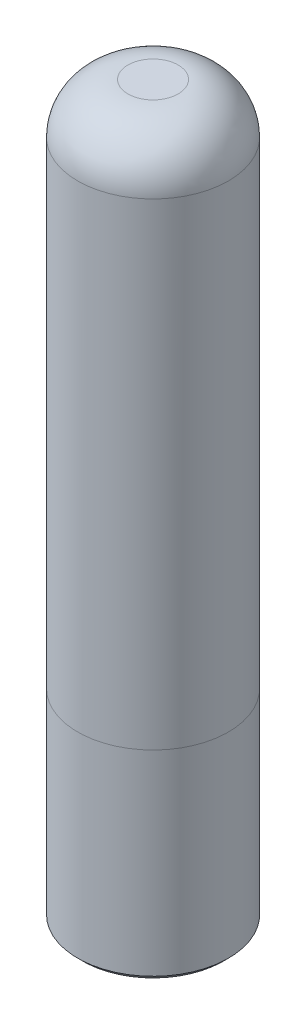
SolidWorks part; units mm, degrees
ref_plane "Front Plane" through (0, 0, 0) normal (0, 0, 1) x (1, 0, 0)
ref_plane "Top Plane" through (0, 0, 0) normal (0, 1, 0) x (1, 0, 0)
ref_plane "Right Plane" through (0, 0, 0) normal (1, 0, 0) x (0, 0, -1)
sketch "Sketch1" plane through (0, 0, 0) normal (0, 1, 0) x (1, 0, 0)
  circle A0 centre (0, 0) radius 1.5
  dimension "D1" = 3
extrude "Boss-Extrude1" add sketch "Sketch1" along normal blind 10.5
fillet "Fillet1" radius 1 1 edges at (0, 10.5, 1.5)
sketch "Sketch2" plane through (0, 0, 0) normal (0, -1, 0) x (1, 0, 0)
  circle A0 centre (0, 0) radius 1.5 construction
  circle A1 centre (0, 0) radius 1.5
extrude "Boss-Extrude2" add sketch "Sketch2" along normal blind 4 separate body
chamfer "Chamfer1" distance 0.1 angle 45 1 edges at (0, -4, -1.5)
